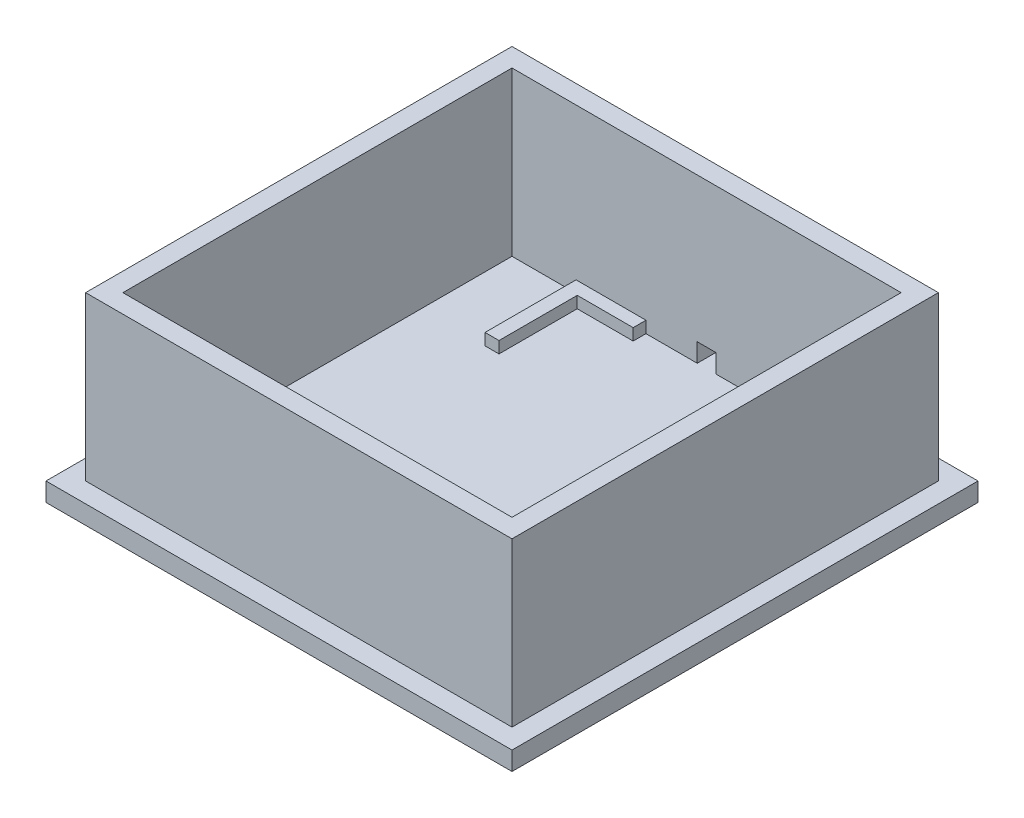
SolidWorks part; units mm, degrees
ref_plane "Front Plane" through (0, 0, 0) normal (0, 0, 1) x (1, 0, 0)
ref_plane "Top Plane" through (0, 0, 0) normal (0, 1, 0) x (1, 0, 0)
ref_plane "Right Plane" through (0, 0, 0) normal (1, 0, 0) x (0, 0, -1)
sketch "Sketch1" plane through (0, 0, 0) normal (0, 1, 0) x (1, 0, 0)
  line L1 (-50, -50) -> (50, -50)
  line L2 (-50, -50) -> (-50, 50)
  line L3 (-50, 50) -> (50, 50)
  line L4 (50, -50) -> (50, 50)
  line L5 (-50, -50) -> (50, 50) construction
  line L6 (-50, 50) -> (50, -50) construction
  point P0 (0, 0)
  dimension "D1" = 100
extrude "Boss-Extrude1" add sketch "Sketch1" along normal blind 4
sketch "Sketch2" plane through (0, 4, 0) normal (0, 1, 0) x (1, 0, 0)
  line L4 (41.75, -41.75) -> (41.75, 41.75)
  line L5 (41.75, 41.75) -> (-41.75, 41.75)
  line L6 (-41.75, 41.75) -> (-41.75, -41.75)
  line L7 (-41.75, -41.75) -> (41.75, -41.75)
  line L8 (45.75, -45.75) -> (45.75, 45.75)
  line L9 (45.75, 45.75) -> (-45.75, 45.75)
  line L10 (-45.75, 45.75) -> (-45.75, -45.75)
  line L11 (-45.75, -45.75) -> (45.75, -45.75)
  line L12 (45.75, -45.75) -> (45.75, 45.75)
  line L13 (45.75, 45.75) -> (-45.75, 45.75)
  line L14 (-45.75, 45.75) -> (-45.75, -45.75)
  line L15 (-45.75, -45.75) -> (45.75, -45.75)
  dimension "D1" = 4.25
  dimension "D2" = 4
extrude "Boss-Extrude2" add sketch "Sketch2" along normal blind 35
sketch "Sketch3" plane through (0, 0, -45.75) normal (0, 0, -1) x (-1, 0, 0)
  line L0 (-50, 4) -> (50, 4) construction
  line L1 (-2, 8) -> (2, 8)
  line L2 (-2, 8) -> (-2, 4)
  line L3 (-2, 4) -> (2, 4)
  line L4 (2, 8) -> (2, 4)
  line L5 (-2, 8) -> (2, 4) construction
  line L6 (-2, 4) -> (2, 8) construction
  point P0 (0, 6)
  point P7 (0, 0)
  dimension "D1" = 4
extrude "Cut-Extrude1" cut sketch "Sketch3" against normal up to surface (4 mm away) up to face at (0, 21.5, -41.75)
sketch "Sketch4" plane through (0, 4, 0) normal (0, 1, 0) x (1, 0, 0)
  line L0 (41.75, 41.75) -> (-41.75, 41.75) construction
  line L1 (-25, -39) -> (25, -39)
  line L2 (-25, -39) -> (-25, 39)
  line L3 (-25, 39) -> (25, 39)
  line L4 (25, -39) -> (25, 39)
  line L5 (-25, -39) -> (25, 39) construction
  line L6 (-25, 39) -> (25, -39) construction
  line L7 (-13, 22.21) -> (-28, 22.21)
  line L8 (-13, 22.21) -> (-13, 41.75)
  line L9 (-13, 41.75) -> (-28, 41.75)
  line L10 (-28, 22.21) -> (-28, 41.75)
  line L11 (-13, 22.21) -> (-28, 41.75) construction
  line L12 (-13, 41.75) -> (-28, 22.21) construction
  line L13 (-41.75, -41.75) -> (41.75, -41.75) construction
  line L14 (13, 22.21) -> (28, 22.21)
  line L15 (13, 22.21) -> (13, 41.75)
  line L16 (13, 41.75) -> (28, 41.75)
  line L17 (28, 22.21) -> (28, 41.75)
  line L18 (13, 22.21) -> (28, 41.75) construction
  line L19 (13, 41.75) -> (28, 22.21) construction
  line L20 (-28, -22.21) -> (-13, -22.21)
  line L21 (-28, -22.21) -> (-28, -41.75)
  line L22 (-28, -41.75) -> (-13, -41.75)
  line L23 (-13, -22.21) -> (-13, -41.75)
  line L24 (-28, -22.21) -> (-13, -41.75) construction
  line L25 (-28, -41.75) -> (-13, -22.21) construction
  line L27 (28, -22.21) -> (13, -22.21)
  line L28 (28, -22.21) -> (28, -41.75)
  line L29 (28, -41.75) -> (13, -41.75)
  line L30 (13, -22.21) -> (13, -41.75)
  line L31 (28, -22.21) -> (13, -41.75) construction
  line L32 (28, -41.75) -> (13, -22.21) construction
  point P0 (0, 0)
  point P6 (-20.5, 31.98)
  point P13 (20.5, 31.98)
  point P18 (-20.5, -31.98)
  point P25 (20.5, -31.98)
  point P30 (-27.8389, 25.4589)
  line M17 (-41.75, -41.75) -> (41.75, -41.75)
  line M19 (41.75, 41.75) -> (2, 41.75)
  line M27 (-2, 41.75) -> (-41.75, 41.75)
  dimension "D1" = 78
  dimension "D2" = 50
  dimension "D3" = 3
  dimension "D4" = 15
extrude "Boss-Extrude3" add sketch "Sketch4" along normal blind 2.5 contours L10 L7 L2 L3 L8 M27 | L14 L17 L15 L3 L4 M19 | L1 L30 L28 L27 L4 M17 | L23 L1 L2 L20 L21 M17
